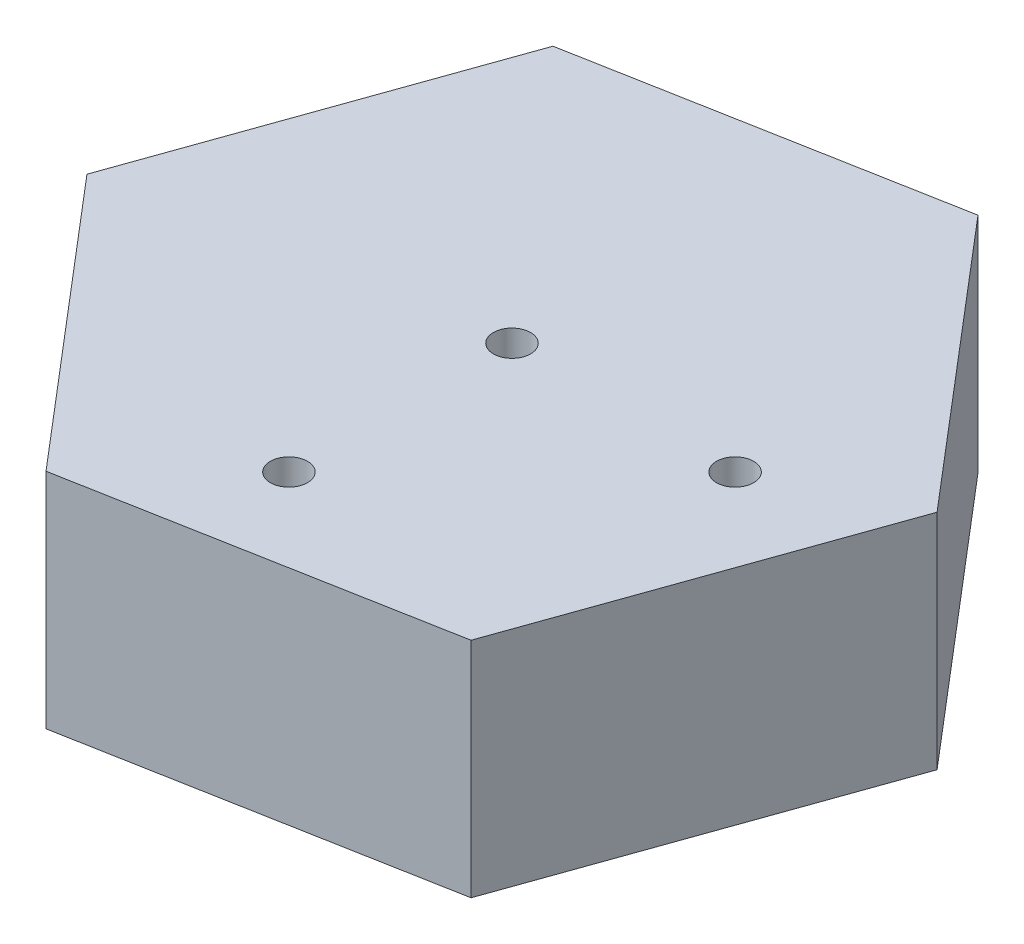
SolidWorks part; units mm, degrees
material "ABS"
ref_plane "Alzado" through (0, 0, 0) normal (0, 0, 1) x (1, 0, 0)
ref_plane "Planta" through (0, 0, 0) normal (0, 1, 0) x (1, 0, 0)
ref_plane "Vista lateral" through (0, 0, 0) normal (1, 0, 0) x (0, 0, -1)
sketch "Croquis1" plane through (0, 0, 0) normal (0, 1, 0) x (1, 0, 0)
  line L1 (-31.8383, 37.3451) -> (-48.2609, -8.9003)
  line L2 (-48.2609, -8.9003) -> (-16.4226, -46.2453)
  line L3 (-16.4226, -46.2453) -> (31.8383, -37.3451)
  line L4 (31.8383, -37.3451) -> (48.2609, 8.9003)
  line L5 (48.2609, 8.9003) -> (16.4226, 46.2453)
  line L6 (16.4226, 46.2453) -> (-31.8383, 37.3451)
  circle A0 centre (0, 0) radius 42.5 construction
  dimension "D1" = 85
extrude "Saliente-Extruir1" add sketch "Croquis1" along normal blind 30
sketch "Croquis2" plane through (0, 30, 0) normal (0, 1, 0) x (1, 0, 0)
  circle A0 centre (0, 0) radius 2.5
  dimension "D1" = 5
extrude "Cortar-Extruir1" cut sketch "Croquis2" against normal blind 5
sketch "Croquis3" plane through (0, 0, 0) normal (0, -1, 0) x (1, 0, 0)
  circle A0 centre (0, 30) radius 2.5
  circle A1 centre (30, 0) radius 2.5
  dimension "D1" = 5
  dimension "D2" = 5
  dimension "D3" = 30
  dimension "D4" = 30
extrude "Cortar-Extruir2" cut sketch "Croquis3" against normal through all
